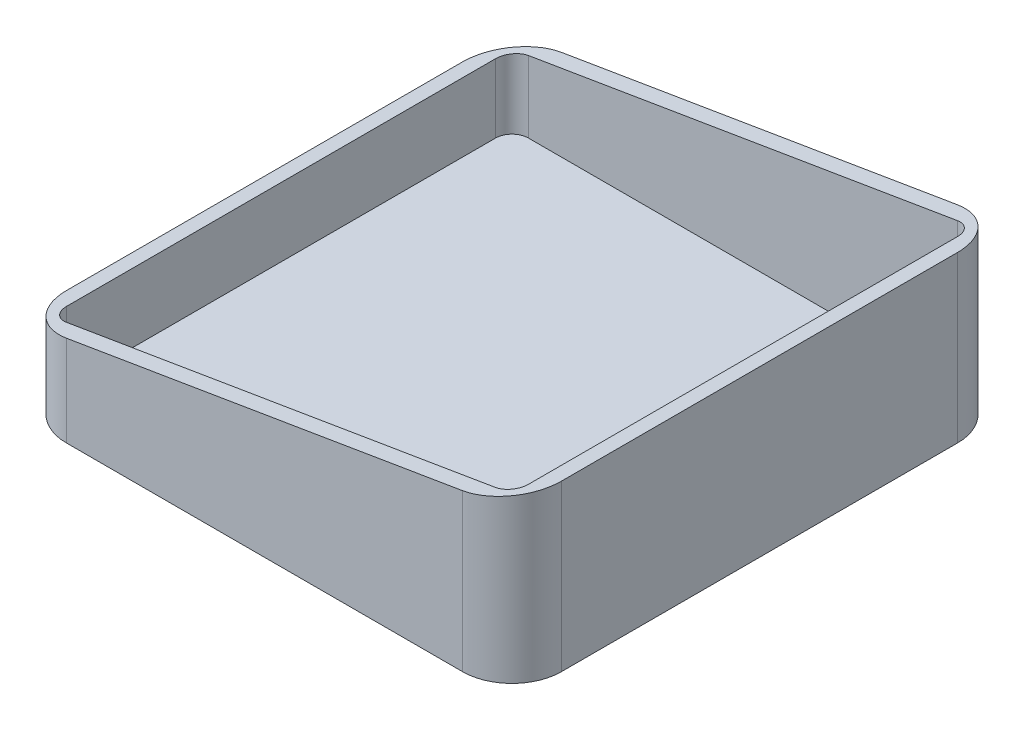
SolidWorks part; units mm, degrees
material "Custom Plastic"
ref_plane "Front Plane" through (0, 0, 0) normal (0, 0, 1) x (1, 0, 0)
ref_plane "Top Plane" through (0, 0, 0) normal (0, 1, 0) x (1, 0, 0)
ref_plane "Right Plane" through (0, 0, 0) normal (1, 0, 0) x (0, 0, -1)
sketch "Sketch1" plane through (0, 0, 0) normal (0, 0, 1) x (1, 0, 0)
  line L0 (-150, -16.6216) -> (150, -16.6216)
  line L1 (150, -16.6216) -> (150, 83.3784)
  line L2 (150, 83.3784) -> (-150, 33.3784)
  line L3 (-150, 33.3784) -> (-150, -16.6216)
  dimension "D1" = 300
  dimension "D2" = 100
  dimension "D3" = 50
  dimension "D4" = 90
extrude "Boss-Extrude1" add sketch "Sketch1" along normal blind 300
shell "Shell1" thickness 10
fillet "Fillet1" radius 30 4 edges at (-150, 8.3784, 0) (150, 33.3784, 0) (150, 33.3784, 300) (-150, 8.3784, 300)
fillet "Fillet2" radius 10 4 edges at (-140, 14.2117, 10) (-140, 14.2117, 290) (140, 37.545, 290) (140, 37.545, 10)
